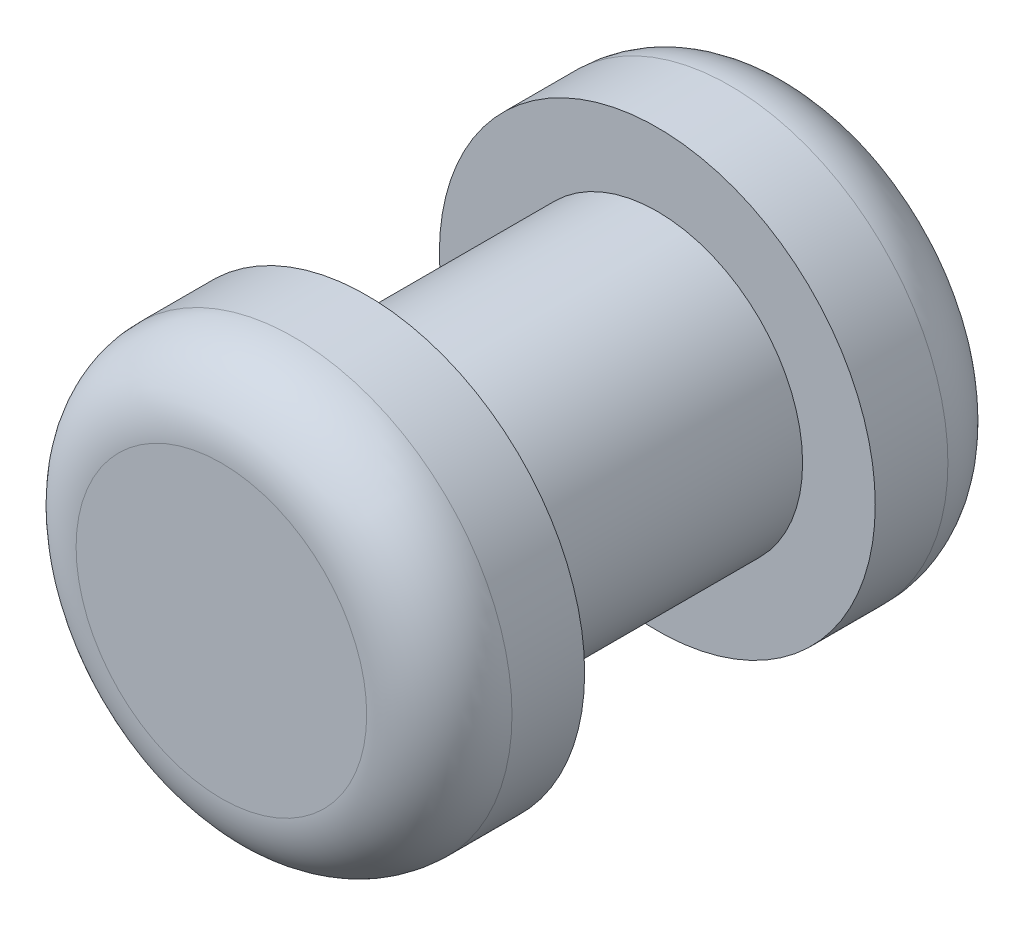
SolidWorks part; units mm, degrees
material "Plain Carbon Steel"
ref_plane "Front Plane" through (0, 0, 0) normal (0, 0, 1) x (1, 0, 0)
ref_plane "Top Plane" through (0, 0, 0) normal (0, 1, 0) x (1, 0, 0)
ref_plane "Right Plane" through (0, 0, 0) normal (1, 0, 0) x (0, 0, -1)
sketch "Sketch1" plane through (0, 0, 0) normal (1, 0, 0) x (0, 0, -1)
  line L0 (1, 0) -> (-1, 0)
  line L1 (-1, 0) -> (-1, 0.75)
  line L2 (-1, 0.75) -> (-0.5, 0.75)
  line L3 (-0.5, 0.75) -> (-0.5, 0.5)
  line L4 (-0.5, 0.5) -> (0.5, 0.5)
  line L5 (0.5, 0.5) -> (0.5, 0.75)
  line L6 (0.5, 0.75) -> (1, 0.75)
  line L7 (1, 0.75) -> (1, 0)
  line L8 (0, 0) -> (-2.3886, 0) construction
  point P4 (0, 0)
  dimension "D1" = 2
  dimension "D2" = 1.5
  dimension "D3" = 0.5
  dimension "D4" = 1
revolve "Revolve1" add sketch "Sketch1" angle 360 about L8
fillet "Fillet1" radius 0.25 2 edges at (-0.75, 0, -1) (-0.75, 0, 1)
